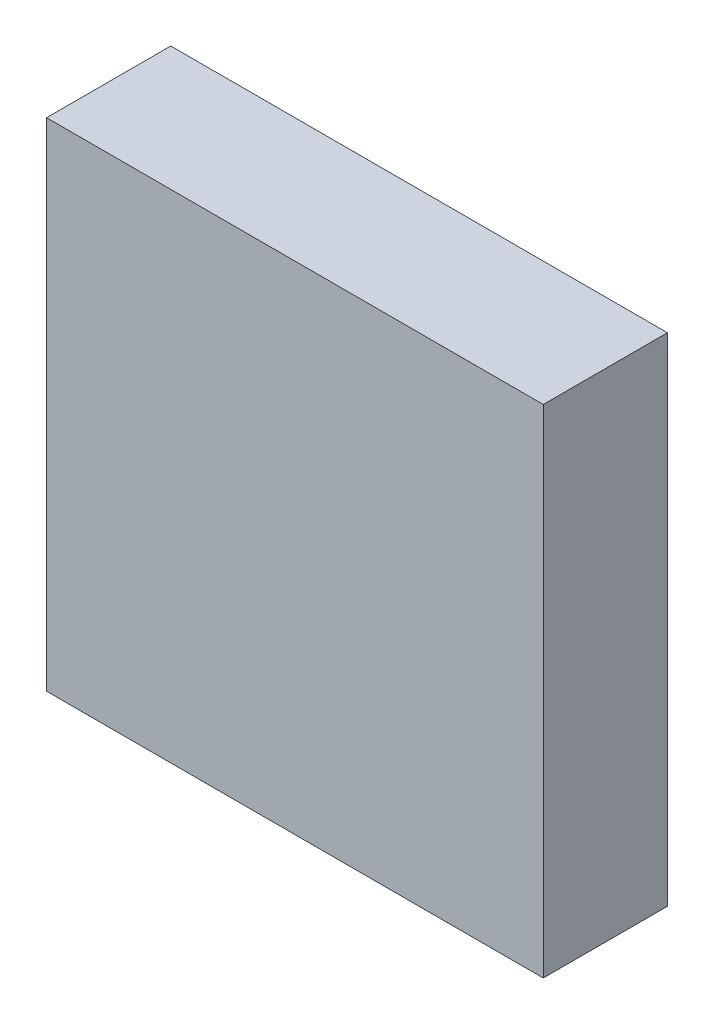
SolidWorks part; units mm, degrees
ref_plane "Front Plane" through (0, 0, 0) normal (0, 0, 1) x (1, 0, 0)
ref_plane "Top Plane" through (0, 0, 0) normal (0, 1, 0) x (1, 0, 0)
ref_plane "Right Plane" through (0, 0, 0) normal (1, 0, 0) x (0, 0, -1)
sketch "Sketch1" plane through (0, 0, 0) normal (0, 0, 1) x (1, 0, 0)
  line L1 (0, 0) -> (50.8, 0)
  line L2 (0, 0) -> (0, 50.8)
  line L3 (0, 50.8) -> (50.8, 50.8)
  line L4 (50.8, 0) -> (50.8, 50.8)
  dimension "D1" = 50.8
  dimension "D2" = 50.8
extrude "Boss-Extrude1" add sketch "Sketch1" along normal blind 12.7
